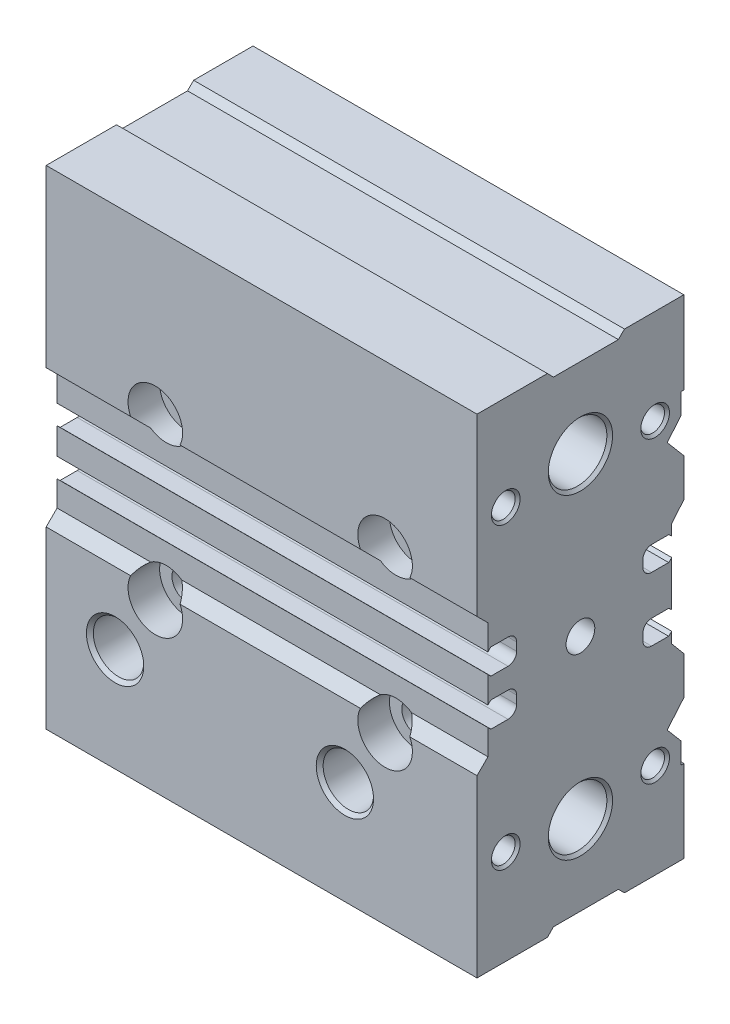
SolidWorks part; units mm, degrees
ref_plane "Front" through (0, 0, 0) normal (0, 0, 1) x (1, 0, 0)
ref_plane "Top" through (0, 0, 0) normal (0, 1, 0) x (1, 0, 0)
ref_plane "Right" through (0, 0, 0) normal (1, 0, 0) x (0, 0, -1)
ref_plane "Plane1" through (0, 0, 0) normal (1, 0, 0) x (0, 0, -1)
sketch "Sketch1" plane through (0, 0, 0) normal (1, 0, 0) x (0, 0, -1)
  line L0 (-18, -42.5) -> (-5.75, -42.5)
  line L1 (-5.75, -42.5) -> (-4.6875, -41.4375)
  line L2 (-4.6875, -41.4375) -> (6.6042, -41.4375)
  line L3 (6.6042, -41.4375) -> (7.6667, -42.5)
  line L4 (7.6667, -42.5) -> (18, -42.5)
  line L5 (18, -42.5) -> (18, -28.1522)
  line L6 (18, -28.1522) -> (17.5, -28.1522)
  line L7 (17.5, -28.1522) -> (17.5, -24.5)
  line L8 (17.5, -24.5) -> (15.1, -21.6667)
  line L9 (15.1, -21.6667) -> (18, -18.2431)
  line L10 (18, -18.2431) -> (18, -11.5959)
  line L11 (18, -11.5959) -> (15.8824, -9.0722)
  line L12 (15.8824, -9.0722) -> (15.8824, -7.1556)
  line L13 (15.3538, -7.6556) -> (12.3824, -7.6556)
  line L14 (10.8824, -6.1556) -> (10.8824, -4.9556)
  line L15 (12.3824, -3.4556) -> (15.3538, -3.4556)
  line L16 (15.8824, -3.9556) -> (15.8824, 3.9556)
  line L17 (15.3538, 3.4556) -> (12.3824, 3.4556)
  line L18 (10.8824, 4.9556) -> (10.8824, 6.1556)
  line L19 (12.3824, 7.6556) -> (15.3538, 7.6556)
  line L20 (15.8824, 7.1556) -> (15.8824, 9.0722)
  line L21 (15.8824, 9.0722) -> (18, 11.5959)
  line L22 (18, 11.5959) -> (18, 18.2431)
  line L23 (18, 18.2431) -> (15.1, 21.6667)
  line L24 (15.1, 21.6667) -> (17.5, 24.5)
  line L25 (17.5, 24.5) -> (17.5, 28.1522)
  line L26 (17.5, 28.1522) -> (18, 28.1522)
  line L27 (18, 28.1522) -> (18, 42.5)
  line L28 (18, 42.5) -> (7.6667, 42.5)
  line L29 (7.6667, 42.5) -> (6.6042, 41.4375)
  line L30 (6.6042, 41.4375) -> (-4.6875, 41.4375)
  line L31 (-4.6875, 41.4375) -> (-5.75, 42.5)
  line L32 (-5.75, 42.5) -> (-18, 42.5)
  line L33 (-18, 42.5) -> (-18, 12)
  line L34 (-18, 12) -> (-16.1, 10.1)
  line L35 (-16.1, 10.1) -> (-16.1, 5.7)
  line L36 (-15.5714, 6.2) -> (-12.6, 6.2)
  line L37 (-11.1, 4.7) -> (-11.1, 3.3)
  line L38 (-12.6, 1.8) -> (-15.5714, 1.8)
  line L39 (-16.1, 2.3) -> (-16.1, -2.3)
  line L40 (-15.5714, -1.8) -> (-12.6, -1.8)
  line L41 (-11.1, -3.3) -> (-11.1, -4.7)
  line L42 (-12.6, -6.2) -> (-15.5714, -6.2)
  line L43 (-16.1, -5.7) -> (-16.1, -10.1)
  line L44 (-16.1, -10.1) -> (-18, -12)
  line L45 (-18, -12) -> (-18, -42.5)
  arc A0 (15.8824, -7.1556) -> (15.3538, -7.6556) centre (13.8681, -5.5556) cw
  arc A1 (12.3824, -7.6556) -> (10.8824, -6.1556) centre (12.3824, -6.1556) cw
  arc A2 (10.8824, -4.9556) -> (12.3824, -3.4556) centre (12.3824, -4.9556) cw
  arc A3 (15.3538, -3.4556) -> (15.8824, -3.9556) centre (13.8681, -5.5556) cw
  arc A4 (15.8824, 3.9556) -> (15.3538, 3.4556) centre (13.8681, 5.5556) cw
  arc A5 (12.3824, 3.4556) -> (10.8824, 4.9556) centre (12.3824, 4.9556) cw
  arc A6 (10.8824, 6.1556) -> (12.3824, 7.6556) centre (12.3824, 6.1556) cw
  arc A7 (15.3538, 7.6556) -> (15.8824, 7.1556) centre (13.8681, 5.5556) cw
  arc A8 (-16.1, 5.7) -> (-15.5714, 6.2) centre (-14.0857, 4.1) cw
  arc A9 (-12.6, 6.2) -> (-11.1, 4.7) centre (-12.6, 4.7) cw
  arc A10 (-11.1, 3.3) -> (-12.6, 1.8) centre (-12.6, 3.3) cw
  arc A11 (-15.5714, 1.8) -> (-16.1, 2.3) centre (-14.0857, 3.9) cw
  arc A12 (-16.1, -2.3) -> (-15.5714, -1.8) centre (-14.0857, -3.9) cw
  arc A13 (-12.6, -1.8) -> (-11.1, -3.3) centre (-12.6, -3.3) cw
  arc A14 (-11.1, -4.7) -> (-12.6, -6.2) centre (-12.6, -4.7) cw
  arc A15 (-15.5714, -6.2) -> (-16.1, -5.7) centre (-14.0857, -4.1) cw
extrude "Boss-Extrude1" add sketch "Sketch1" along normal blind 75
ref_plane "Plane2" through (0, 0, 0) normal (0, 0, 1) x (1, 0, 0)
sketch "Sketch2" plane through (0, 0, 0) normal (0, 0, 1) x (1, 0, 0)
  line L0 (0, 27.5) -> (0, 33.1)
  line L1 (0, 33.1) -> (0.5, 32.6)
  line L2 (0.5, 32.6) -> (74.5, 32.6)
  line L3 (74.5, 32.6) -> (75, 33.1)
  line L4 (75, 33.1) -> (75, 27.5)
  line L5 (75, 27.5) -> (0, 27.5)
  line L6 (75, 27.5) -> (0, 27.5) construction
revolve "Cut-Revolve1" cut sketch "Sketch2" angle 360 about L6
ref_plane "Plane3" through (0, 0, 0) normal (0, 0, 1) x (1, 0, 0)
sketch "Sketch3" plane through (0, 0, 0) normal (0, 0, 1) x (1, 0, 0)
  line L0 (0, -27.5) -> (0, -21.9)
  line L1 (0, -21.9) -> (0.5, -22.4)
  line L2 (0.5, -22.4) -> (74.5, -22.4)
  line L3 (74.5, -22.4) -> (75, -21.9)
  line L4 (75, -21.9) -> (75, -27.5)
  line L5 (75, -27.5) -> (0, -27.5)
  line L6 (75, -27.5) -> (0, -27.5) construction
revolve "Cut-Revolve2" cut sketch "Sketch3" angle 360 about L6
ref_plane "Plane4" through (0, 32, 0) normal (0, 1, 0) x (-1, 0, 0)
sketch "Sketch4" plane through (0, 32, 0) normal (0, 1, 0) x (-1, 0, 0)
  line L0 (-11, -18) -> (-13.5, -18)
  line L1 (-13.5, -18) -> (-13.067, -17.567)
  line L2 (-13.067, -17.567) -> (-13.067, -10.0934)
  line L3 (-13.067, -10.0934) -> (-11, -8.9)
  line L4 (-11, -8.9) -> (-11, -18)
  line L5 (-11, -8.9) -> (-11, -18) construction
revolve "Cut-Revolve3" cut sketch "Sketch4" angle 360 about L5
cosmetic thread "Cosmetic Thread1" parameters "D1"=6.567, "D2"=5
ref_plane "Plane5" through (0, 32, 0) normal (0, 1, 0) x (-1, 0, 0)
sketch "Sketch5" plane through (0, 32, 0) normal (0, 1, 0) x (-1, 0, 0)
  line L0 (-61, -18) -> (-63.5, -18)
  line L1 (-63.5, -18) -> (-63.067, -17.567)
  line L2 (-63.067, -17.567) -> (-63.067, -10.0934)
  line L3 (-63.067, -10.0934) -> (-61, -8.9)
  line L4 (-61, -8.9) -> (-61, -18)
  line L5 (-61, -8.9) -> (-61, -18) construction
revolve "Cut-Revolve4" cut sketch "Sketch5" angle 360 about L5
cosmetic thread "Cosmetic Thread2" parameters "D1"=6.567, "D2"=5
ref_plane "Plane6" through (0, -32, 0) normal (0, 1, 0) x (-1, 0, 0)
sketch "Sketch6" plane through (0, -32, 0) normal (0, 1, 0) x (-1, 0, 0)
  line L0 (-11, -18) -> (-13.5, -18)
  line L1 (-13.5, -18) -> (-13.067, -17.567)
  line L2 (-13.067, -17.567) -> (-13.067, -10.0934)
  line L3 (-13.067, -10.0934) -> (-11, -8.9)
  line L4 (-11, -8.9) -> (-11, -18)
  line L5 (-11, -8.9) -> (-11, -18) construction
revolve "Cut-Revolve5" cut sketch "Sketch6" angle 360 about L5
cosmetic thread "Cosmetic Thread3" parameters "D1"=6.567, "D2"=5
ref_plane "Plane7" through (0, -32, 0) normal (0, 1, 0) x (-1, 0, 0)
sketch "Sketch7" plane through (0, -32, 0) normal (0, 1, 0) x (-1, 0, 0)
  line L0 (-61, -18) -> (-63.5, -18)
  line L1 (-63.5, -18) -> (-63.067, -17.567)
  line L2 (-63.067, -17.567) -> (-63.067, -10.0934)
  line L3 (-63.067, -10.0934) -> (-61, -8.9)
  line L4 (-61, -8.9) -> (-61, -18)
  line L5 (-61, -8.9) -> (-61, -18) construction
revolve "Cut-Revolve6" cut sketch "Sketch7" angle 360 about L5
cosmetic thread "Cosmetic Thread4" parameters "D1"=6.567, "D2"=5
ref_plane "Plane8" through (0, -24.5, 0) normal (0, 1, 0) x (-1, 0, 0)
sketch "Sketch8" plane through (0, -24.5, 0) normal (0, 1, 0) x (-1, 0, 0)
  line L0 (-12, 9.1564) -> (-16.1318, 9.1564)
  line L1 (-16.1318, 9.1564) -> (-16.3892, 17.4003)
  line L2 (-16.3892, 17.4003) -> (-16.9889, 18)
  line L3 (-16.9889, 18) -> (-12, 18)
  line L4 (-12, 18) -> (-12, 9.1564)
  line L5 (-12, 18) -> (-12, 9.1564) construction
revolve "Cut-Revolve7" cut sketch "Sketch8" angle 360 about L5
ref_plane "Plane9" through (0, -24.5, 0) normal (0, 1, 0) x (-1, 0, 0)
sketch "Sketch9" plane through (0, -24.5, 0) normal (0, 1, 0) x (-1, 0, 0)
  line L0 (-52, 9.1564) -> (-56.1318, 9.1564)
  line L1 (-56.1318, 9.1564) -> (-56.3892, 17.4003)
  line L2 (-56.3892, 17.4003) -> (-56.9889, 18)
  line L3 (-56.9889, 18) -> (-52, 18)
  line L4 (-52, 18) -> (-52, 9.1564)
  line L5 (-52, 18) -> (-52, 9.1564) construction
revolve "Cut-Revolve8" cut sketch "Sketch9" angle 360 about L5
ref_plane "Plane10" through (0, 0, 0) normal (0, 1, 0) x (-1, 0, 0)
sketch "Sketch10" plane through (0, 0, 0) normal (0, 1, 0) x (-1, 0, 0)
  line L0 (0, 0) -> (0, -5.1)
  line L1 (0, -5.1) -> (-40, -5.1)
  line L2 (-40, -5.1) -> (-40, 0)
  line L3 (-40, 0) -> (0, 0)
  line L4 (-40, 0) -> (0, 0) construction
revolve "Cut-Revolve9" cut sketch "Sketch10" angle 360 about L4
ref_plane "Plane11" through (12, 0, 0) normal (1, 0, 0) x (0, 0, -1)
sketch "Sketch11" plane through (12, 0, 0) normal (1, 0, 0) x (0, 0, -1)
  line L0 (-11.5, -33.6564) -> (-7.3682, -33.6564)
  line L1 (-7.3682, -33.6564) -> (-7.1108, -41.9003)
  line L2 (-7.1108, -41.9003) -> (-6.5111, -42.5)
  line L3 (-6.5111, -42.5) -> (-11.5, -42.5)
  line L4 (-11.5, -42.5) -> (-11.5, -33.6564)
  line L5 (-11.5, -42.5) -> (-11.5, -33.6564) construction
revolve "Cut-Revolve10" cut sketch "Sketch11" angle 360 about L5
ref_plane "Plane12" through (52, 0, 0) normal (1, 0, 0) x (0, 0, -1)
sketch "Sketch12" plane through (52, 0, 0) normal (1, 0, 0) x (0, 0, -1)
  line L0 (-11.5, -33.6564) -> (-7.3682, -33.6564)
  line L1 (-7.3682, -33.6564) -> (-7.1108, -41.9003)
  line L2 (-7.1108, -41.9003) -> (-6.5111, -42.5)
  line L3 (-6.5111, -42.5) -> (-11.5, -42.5)
  line L4 (-11.5, -42.5) -> (-11.5, -33.6564)
  line L5 (-11.5, -42.5) -> (-11.5, -33.6564) construction
revolve "Cut-Revolve11" cut sketch "Sketch12" angle 360 about L5
ref_plane "Plane13" through (0, 0, 0) normal (0, 0, 1) x (1, 0, 0)
sketch "Sketch13" plane through (0, 0, 0) normal (0, 0, 1) x (1, 0, 0)
  line L0 (65.5566, 0) -> (67, 2.5)
  line L1 (67, 2.5) -> (75, 2.5)
  line L2 (75, 2.5) -> (75, 0)
  line L3 (75, 0) -> (65.5566, 0)
  line L4 (75, 0) -> (65.5566, 0) construction
revolve "Cut-Revolve12" cut sketch "Sketch13" angle 360 about L4
ref_plane "Plane14" through (0, 0, -13) normal (0, 0, 1) x (1, 0, 0)
sketch "Sketch14" plane through (0, 0, -13) normal (0, 0, 1) x (1, 0, 0)
  line L0 (58.2066, 26) -> (59.4, 28.067)
  line L1 (59.4, 28.067) -> (74.567, 28.067)
  line L2 (74.567, 28.067) -> (75, 28.5)
  line L3 (75, 28.5) -> (75, 26)
  line L4 (75, 26) -> (58.2066, 26)
  line L5 (75, 26) -> (58.2066, 26) construction
revolve "Cut-Revolve13" cut sketch "Sketch14" angle 360 about L5
cosmetic thread "Cosmetic Thread5" parameters "D1"=12.567, "D2"=5
ref_plane "Plane15" through (0, 0, -13) normal (0, 0, 1) x (1, 0, 0)
sketch "Sketch15" plane through (0, 0, -13) normal (0, 0, 1) x (1, 0, 0)
  line L0 (58.2066, -26) -> (59.4, -23.933)
  line L1 (59.4, -23.933) -> (74.567, -23.933)
  line L2 (74.567, -23.933) -> (75, -23.5)
  line L3 (75, -23.5) -> (75, -26)
  line L4 (75, -26) -> (58.2066, -26)
  line L5 (75, -26) -> (58.2066, -26) construction
revolve "Cut-Revolve14" cut sketch "Sketch15" angle 360 about L5
cosmetic thread "Cosmetic Thread6" parameters "D1"=12.567, "D2"=5
ref_plane "Plane16" through (0, 0, 13) normal (0, 0, 1) x (1, 0, 0)
sketch "Sketch16" plane through (0, 0, 13) normal (0, 0, 1) x (1, 0, 0)
  line L0 (58.2066, 26) -> (59.4, 28.067)
  line L1 (59.4, 28.067) -> (74.567, 28.067)
  line L2 (74.567, 28.067) -> (75, 28.5)
  line L3 (75, 28.5) -> (75, 26)
  line L4 (75, 26) -> (58.2066, 26)
  line L5 (75, 26) -> (58.2066, 26) construction
revolve "Cut-Revolve15" cut sketch "Sketch16" angle 360 about L5
cosmetic thread "Cosmetic Thread7" parameters "D1"=12.567, "D2"=5
ref_plane "Plane17" through (0, 0, 13) normal (0, 0, 1) x (1, 0, 0)
sketch "Sketch17" plane through (0, 0, 13) normal (0, 0, 1) x (1, 0, 0)
  line L0 (58.2066, -26) -> (59.4, -23.933)
  line L1 (59.4, -23.933) -> (74.567, -23.933)
  line L2 (74.567, -23.933) -> (75, -23.5)
  line L3 (75, -23.5) -> (75, -26)
  line L4 (75, -26) -> (58.2066, -26)
  line L5 (75, -26) -> (58.2066, -26) construction
revolve "Cut-Revolve16" cut sketch "Sketch17" angle 360 about L5
cosmetic thread "Cosmetic Thread8" parameters "D1"=12.567, "D2"=5
ref_plane "Plane18" through (19, 0, 0) normal (1, 0, 0) x (0, 0, -1)
sketch "Sketch18" plane through (19, 0, 0) normal (1, 0, 0) x (0, 0, -1)
  line L0 (-18, 14) -> (-18, 18.75)
  line L1 (-18, 18.75) -> (-12.5, 18.75)
  line L2 (-12.5, 18.75) -> (-12.5, 16.6)
  line L3 (-12.5, 16.6) -> (5.3072, 16.6)
  line L4 (5.3072, 16.6) -> (5.3072, 16.4585)
  line L5 (5.3072, 16.4585) -> (17.4585, 16.4585)
  line L6 (17.4585, 16.4585) -> (18, 17)
  line L7 (18, 17) -> (18, 14)
  line L8 (18, 14) -> (-18, 14)
  line L9 (18, 14) -> (-18, 14) construction
revolve "Cut-Revolve17" cut sketch "Sketch18" angle 360 about L9
cosmetic thread "Cosmetic Thread9" parameters "D1"=11.4585, "D2"=6
ref_plane "Plane19" through (19, 0, 0) normal (1, 0, 0) x (0, 0, -1)
sketch "Sketch19" plane through (19, 0, 0) normal (1, 0, 0) x (0, 0, -1)
  line L0 (-18, -14) -> (-18, -9.25)
  line L1 (-18, -9.25) -> (-12.5, -9.25)
  line L2 (-12.5, -9.25) -> (-12.5, -11.4)
  line L3 (-12.5, -11.4) -> (5.3072, -11.4)
  line L4 (5.3072, -11.4) -> (5.3072, -11.5415)
  line L5 (5.3072, -11.5415) -> (17.4585, -11.5415)
  line L6 (17.4585, -11.5415) -> (18, -11)
  line L7 (18, -11) -> (18, -14)
  line L8 (18, -14) -> (-18, -14)
  line L9 (18, -14) -> (-18, -14) construction
revolve "Cut-Revolve18" cut sketch "Sketch19" angle 360 about L9
cosmetic thread "Cosmetic Thread10" parameters "D1"=11.4585, "D2"=6
ref_plane "Plane20" through (59, 0, 0) normal (1, 0, 0) x (0, 0, -1)
sketch "Sketch20" plane through (59, 0, 0) normal (1, 0, 0) x (0, 0, -1)
  line L0 (-18, -14) -> (-18, -9.25)
  line L1 (-18, -9.25) -> (-12.5, -9.25)
  line L2 (-12.5, -9.25) -> (-12.5, -11.4)
  line L3 (-12.5, -11.4) -> (5.3072, -11.4)
  line L4 (5.3072, -11.4) -> (5.3072, -11.5415)
  line L5 (5.3072, -11.5415) -> (17.4585, -11.5415)
  line L6 (17.4585, -11.5415) -> (18, -11)
  line L7 (18, -11) -> (18, -14)
  line L8 (18, -14) -> (-18, -14)
  line L9 (18, -14) -> (-18, -14) construction
revolve "Cut-Revolve19" cut sketch "Sketch20" angle 360 about L9
cosmetic thread "Cosmetic Thread11" parameters "D1"=11.4585, "D2"=6
ref_plane "Plane21" through (59, 0, 0) normal (1, 0, 0) x (0, 0, -1)
sketch "Sketch21" plane through (59, 0, 0) normal (1, 0, 0) x (0, 0, -1)
  line L0 (-18, 14) -> (-18, 18.75)
  line L1 (-18, 18.75) -> (-12.5, 18.75)
  line L2 (-12.5, 18.75) -> (-12.5, 16.6)
  line L3 (-12.5, 16.6) -> (5.3072, 16.6)
  line L4 (5.3072, 16.6) -> (5.3072, 16.4585)
  line L5 (5.3072, 16.4585) -> (17.4585, 16.4585)
  line L6 (17.4585, 16.4585) -> (18, 17)
  line L7 (18, 17) -> (18, 14)
  line L8 (18, 14) -> (-18, 14)
  line L9 (18, 14) -> (-18, 14) construction
revolve "Cut-Revolve20" cut sketch "Sketch21" angle 360 about L9
cosmetic thread "Cosmetic Thread12" parameters "D1"=11.4585, "D2"=6
